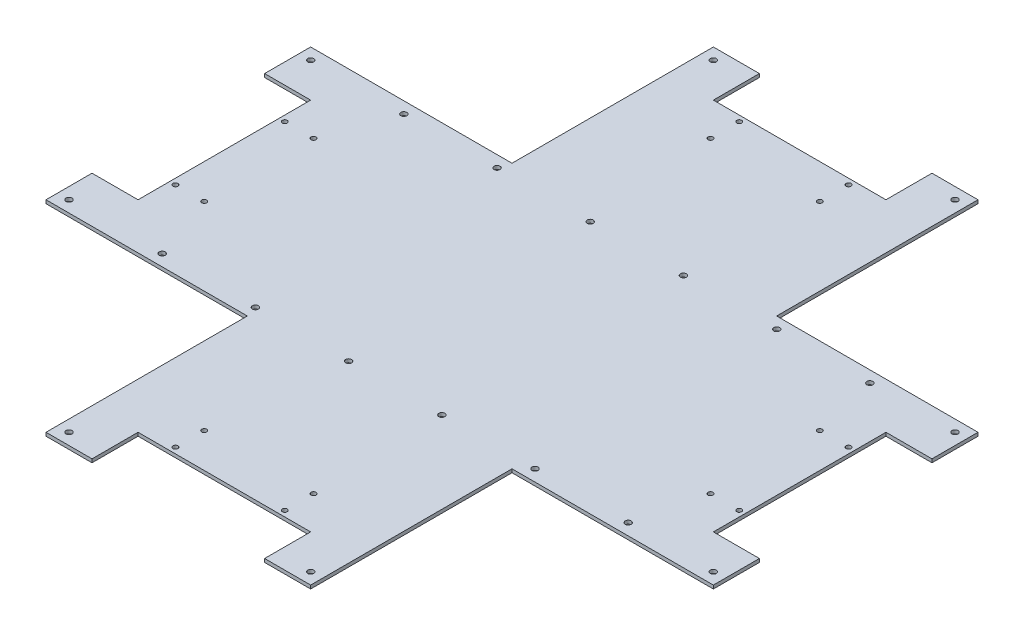
SolidWorks part; units mm, degrees
ref_plane "前视基准面" through (0, 0, 0) normal (0, 0, 1) x (1, 0, 0)
ref_plane "上视基准面" through (0, 0, 0) normal (0, 1, 0) x (1, 0, 0)
ref_plane "右视基准面" through (0, 0, 0) normal (1, 0, 0) x (0, 0, -1)
sketch "草图1" plane through (0, 0, 0) normal (0, 1, 0) x (1, 0, 0)
  line L0 (-290, -115) -> (290, 115) construction
  line L1 (-115, 290) -> (115, 290)
  line L2 (-115, 290) -> (-115, -290)
  line L3 (-115, -290) -> (115, -290)
  line L4 (115, 290) -> (115, -290)
  line L5 (-290, 115) -> (290, 115)
  line L6 (-290, 115) -> (-290, -115)
  line L7 (-290, -115) -> (290, -115)
  line L8 (290, 115) -> (290, -115)
  line L9 (-290, 115) -> (290, -115) construction
  line L10 (115, 290) -> (-115, -290) construction
  line L11 (-115, 290) -> (115, -290) construction
  line L12 (0, 290) -> (0, -290) construction
  line L13 (-290, 0) -> (290, 0) construction
  line L14 (250, 75) -> (290, 75)
  line L15 (-250, -75) -> (-290, -75)
  line L16 (-250, -75) -> (-250, 75)
  line L17 (-250, 75) -> (-290, 75)
  line L18 (-290, -75) -> (-290, 75)
  line L19 (-250, -75) -> (-290, 75) construction
  line L20 (-250, 75) -> (-290, -75) construction
  line L21 (290, -75) -> (290, 75)
  line L22 (250, -75) -> (290, -75)
  line L23 (250, -75) -> (250, 75)
  line L24 (250, 75) -> (290, -75) construction
  line L25 (250, -75) -> (290, 75) construction
  line L26 (-75, -290) -> (75, -290)
  line L27 (-75, 250) -> (75, 250)
  line L28 (-75, 250) -> (-75, 290)
  line L29 (-75, 290) -> (75, 290)
  line L30 (75, 250) -> (75, 290)
  line L31 (-75, 250) -> (75, 290) construction
  line L32 (-75, 290) -> (75, 250) construction
  line L33 (75, -250) -> (75, -290)
  line L34 (-75, -250) -> (75, -250)
  line L35 (-75, -250) -> (-75, -290)
  circle A0 centre (-105, 280) radius 2.6
  circle A1 centre (105, 280) radius 2.6
  circle A2 centre (-105, -280) radius 2.6
  circle A3 centre (105, -280) radius 2.6
  circle A4 centre (280, 105) radius 2.6
  circle A5 centre (280, -105) radius 2.6
  circle A6 centre (-280, -105) radius 2.6
  circle A7 centre (-280, 105) radius 2.6
  circle A8 centre (-199, 105) radius 2.6
  circle A9 centre (-199, -105) radius 2.6
  circle A10 centre (-118, 105) radius 2.6
  circle A11 centre (-118, -105) radius 2.6
  circle A12 centre (-37, 105) radius 2.6
  circle A13 centre (-37, -105) radius 2.6
  circle A14 centre (44, 105) radius 2.6
  circle A15 centre (44, -105) radius 2.6
  circle A16 centre (125, 105) radius 2.6
  circle A17 centre (125, -105) radius 2.6
  circle A18 centre (206, 105) radius 2.6
  circle A19 centre (206, -105) radius 2.6
  circle A20 centre (-245, 47.5) radius 2.15
  circle A21 centre (-220, 47.5) radius 2.15
  circle A22 centre (-245, -47.5) radius 2.15
  circle A23 centre (-220, -47.5) radius 2.15
  circle A24 centre (245, -47.5) radius 2.15
  circle A25 centre (220, -47.5) radius 2.15
  circle A26 centre (220, 47.5) radius 2.15
  circle A27 centre (245, 47.5) radius 2.15
  circle A28 centre (-47.5, 245) radius 2.15
  circle A29 centre (-47.5, 220) radius 2.15
  circle A30 centre (47.5, 220) radius 2.15
  circle A31 centre (47.5, 245) radius 2.15
  circle A32 centre (47.5, -220) radius 2.15
  circle A33 centre (47.5, -245) radius 2.15
  circle A34 centre (-47.5, -220) radius 2.15
  circle A35 centre (-47.5, -245) radius 2.15
  point P8 (0, 0)
  point P11 (0, 0)
  point P31 (-270, 0)
  point P64 (270, 0)
  point P85 (0, 270)
  dimension "D7" = 5.2
  dimension "D10" = 5.2
  dimension "D14" = 4.3
  dimension "D15" = 4.3
  dimension "D21" = 4.3
  dimension "D22" = 4.3
  dimension "D24" = 25
  dimension "D1" = 230
  dimension "D2" = 230
  dimension "D3" = 580
  dimension "D4" = 580
  dimension "D5" = 10
  dimension "D6" = 10
  dimension "D8" = 10
  dimension "D9" = 10
  dimension "D12" = 150
  dimension "D13" = 40
  dimension "D16" = 25
  dimension "D17" = 95
  dimension "D18" = 5
  dimension "D19" = 150
  dimension "D20" = 40
  dimension "D23" = 95
  dimension "D25" = 95
  dimension "D26" = 5
  dimension "D27" = 95
  dimension "D11" = 7
extrude "凸台-拉伸1" add sketch "草图1" along normal blind 3 contours L2 L5 L4 L1 A0 A1 | L8 L5 L4 L7 A4 A5 | L2 L7 L4 L5 | L7 L2 L3 L4 A3 A2 | L6 L7 L2 L5 A6 A7
